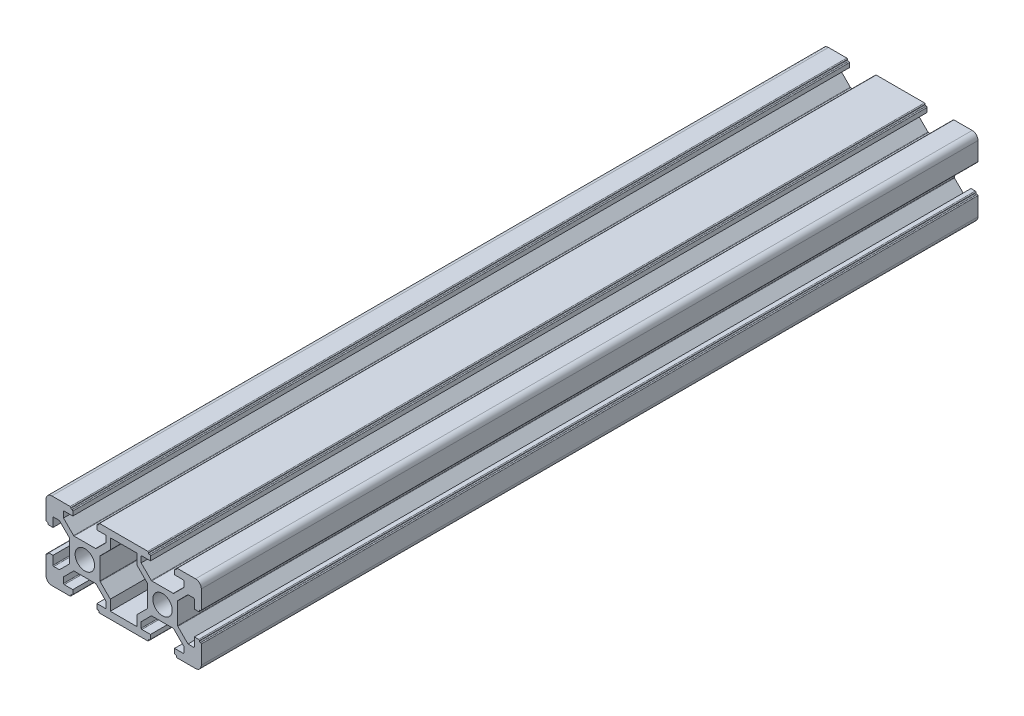
SolidWorks part; units mm, degrees
ref_plane "前视基准面" through (0, 0, 0) normal (0, 0, 1) x (1, 0, 0)
ref_plane "上视基准面" through (0, 0, 0) normal (0, 1, 0) x (1, 0, 0)
ref_plane "右视基准面" through (0, 0, 0) normal (1, 0, 0) x (0, 0, -1)
sketch "Sketch1" plane through (0, 0, 0) normal (0, 0, 1) x (1, 0, 0)
  line L0 (-8.5, 10) -> (-3.8, 10)
  line L3 (-8.5, -10) -> (-3.8, -10)
  line L5 (-10, 8.5) -> (-10, 3.8)
  line L6 (-2.7565, 3.9) -> (2.7565, 3.9)
  line L9 (-2.7565, -3.9) -> (2.7565, -3.9)
  line L10 (3.9, 2.7565) -> (3.9, -2.7565)
  line L11 (-3.9, 2.7565) -> (-3.9, -2.7565)
  line L12 (-3.9586, -2.8979) -> (-6.5607, -5.5)
  line L13 (3.6, 9.7) -> (3.6, 9.8)
  line L14 (3.1, -8.2) -> (5.3, -8.2)
  line L15 (-2.8979, -3.9586) -> (-5.5, -6.5607)
  line L16 (-3.1, -8.2) -> (-3.1, -9.3)
  line L17 (3.1, -8.2) -> (3.1, -9.3)
  line L18 (-5.5, -6.5607) -> (-5.5, -8)
  line L19 (5.5, -6.5607) -> (5.5, -8)
  line L20 (-5.3, -8.2) -> (-3.1, -8.2)
  line L21 (-3.4, -9.5) -> (-3.3, -9.5)
  line L22 (3.8, -10) -> (8.5, -10)
  line L23 (3.3, -9.5) -> (3.4, -9.5)
  line L24 (-3.6, -9.7) -> (-3.6, -9.8)
  line L25 (3.6, -9.7) -> (3.6, -9.8)
  line L26 (-6.5607, -5.5) -> (-8, -5.5)
  line L27 (-9.7, -3.6) -> (-9.8, -3.6)
  line L28 (-9.5, -3.4) -> (-9.5, -3.3)
  line L29 (-8.2, -3.1) -> (-9.3, -3.1)
  line L30 (-8.2, -5.3) -> (-8.2, -3.1)
  line L31 (-10, -3.8) -> (-10, -8.5)
  line L33 (3.8, 10) -> (8.5, 10)
  line L34 (2.8979, -3.9586) -> (5.5, -6.5607)
  line L40 (3.9586, -2.8979) -> (6.5607, -5.5)
  line L41 (3.3, 9.5) -> (3.4, 9.5)
  line L42 (30, 8.5) -> (30, 3.8)
  line L43 (3.1, 8.2) -> (3.1, 9.3)
  line L44 (3.1, 8.2) -> (5.3, 8.2)
  line L45 (5.5, 6.5607) -> (5.5, 8)
  line L46 (2.8979, 3.9586) -> (5.5, 6.5607)
  line L52 (3.9586, 2.8979) -> (6.5607, 5.5)
  line L53 (-3.6, 9.7) -> (-3.6, 9.8)
  line L54 (-3.4, 9.5) -> (-3.3, 9.5)
  line L55 (-3.1, 8.2) -> (-3.1, 9.3)
  line L56 (-5.3, 8.2) -> (-3.1, 8.2)
  line L57 (-5.5, 6.5607) -> (-5.5, 8)
  line L58 (-2.8979, 3.9586) -> (-5.5, 6.5607)
  line L59 (-9.5, 3.4) -> (-9.5, 3.3)
  line L60 (-9.7, 3.6) -> (-9.8, 3.6)
  line L61 (-8.2, 3.1) -> (-9.3, 3.1)
  line L62 (-8.2, 5.3) -> (-8.2, 3.1)
  line L63 (-6.5607, 5.5) -> (-8, 5.5)
  line L64 (-3.9586, 2.8979) -> (-6.5607, 5.5)
  line L65 (29.7, 3.6) -> (29.8, 3.6)
  line L66 (29.5, 3.4) -> (29.5, 3.3)
  line L67 (28.2, 3.1) -> (29.3, 3.1)
  line L68 (28.2, 5.3) -> (28.2, 3.1)
  line L69 (26.5607, 5.5) -> (28, 5.5)
  line L70 (23.9586, 2.8979) -> (26.5607, 5.5)
  line L71 (23.9, 2.7565) -> (23.9, -2.7565)
  line L72 (23.9586, -2.8979) -> (26.5607, -5.5)
  line L73 (26.5607, -5.5) -> (28, -5.5)
  line L74 (28.2, -5.3) -> (28.2, -3.1)
  line L75 (28.2, -3.1) -> (29.3, -3.1)
  line L76 (29.5, -3.4) -> (29.5, -3.3)
  line L77 (29.7, -3.6) -> (29.8, -3.6)
  line L78 (30, -3.8) -> (30, -8.5)
  line L79 (28.5, -10) -> (23.8, -10)
  line L80 (23.6, -9.7) -> (23.6, -9.8)
  line L81 (23.4, -9.5) -> (23.3, -9.5)
  line L82 (23.1, -8.2) -> (23.1, -9.3)
  line L83 (25.3, -8.2) -> (23.1, -8.2)
  line L84 (25.5, -6.5607) -> (25.5, -8)
  line L85 (22.8979, -3.9586) -> (25.5, -6.5607)
  line L86 (22.7565, -3.9) -> (17.2435, -3.9)
  line L87 (17.1021, -3.9586) -> (14.5, -6.5607)
  line L88 (14.5, -6.5607) -> (14.5, -8)
  line L89 (16.9, -8.2) -> (14.7, -8.2)
  line L90 (16.9, -8.2) -> (16.9, -9.3)
  line L91 (16.7, -9.5) -> (16.6, -9.5)
  line L92 (16.4, -9.7) -> (16.4, -9.8)
  line L93 (16.2, -10) -> (11.5, -10)
  line L94 (13.4393, 5.5) -> (13.4393, 8.2)
  line L96 (6.5607, 5.5) -> (6.5607, 8.2)
  line L97 (6.5607, 8.2) -> (13.4393, 8.2)
  line L99 (16.0414, -2.8979) -> (13.4393, -5.5)
  line L100 (16.1, 2.7565) -> (16.1, -2.7565)
  line L101 (16.0414, 2.8979) -> (13.4393, 5.5)
  line L107 (16.2, 10) -> (11.5, 10)
  line L108 (16.4, 9.7) -> (16.4, 9.8)
  line L109 (16.7, 9.5) -> (16.6, 9.5)
  line L110 (16.9, 8.2) -> (16.9, 9.3)
  line L111 (16.9, 8.2) -> (14.7, 8.2)
  line L112 (14.5, 6.5607) -> (14.5, 8)
  line L113 (17.1021, 3.9586) -> (14.5, 6.5607)
  line L114 (22.7565, 3.9) -> (17.2435, 3.9)
  line L115 (22.8979, 3.9586) -> (25.5, 6.5607)
  line L116 (25.5, 6.5607) -> (25.5, 8)
  line L117 (25.3, 8.2) -> (23.1, 8.2)
  line L118 (23.1, 8.2) -> (23.1, 9.3)
  line L119 (23.4, 9.5) -> (23.3, 9.5)
  line L120 (23.6, 9.7) -> (23.6, 9.8)
  line L121 (28.5, 10) -> (23.8, 10)
  line L122 (13.4393, -5.5) -> (13.4393, -8.2)
  line L124 (6.5607, -5.5) -> (6.5607, -8.2)
  line L125 (6.5607, -8.2) -> (13.4393, -8.2)
  line L127 (8.5, 10) -> (11.5, 10)
  line L128 (8.5, -10) -> (11.5, -10)
  arc A3 (-8.5, -10) -> (-10, -8.5) centre (-8.5, -8.5) cw
  arc A4 (-10, 8.5) -> (-8.5, 10) centre (-8.5, 8.5) cw
  arc A5 (3.4, -9.5) -> (3.6, -9.7) centre (3.4, -9.7) cw
  arc A6 (3.8, -10) -> (3.6, -9.8) centre (3.8, -9.8) cw
  arc A7 (3.3, -9.5) -> (3.1, -9.3) centre (3.3, -9.3) cw
  arc A8 (5.3, -8.2) -> (5.5, -8) centre (5.3, -8) ccw
  arc A9 (-3.9, -2.7565) -> (-3.9586, -2.8979) centre (-4.1, -2.7565) cw
  arc A10 (-3.9, 2.7565) -> (-3.9586, 2.8979) centre (-4.1, 2.7565) ccw
  arc A11 (-2.7565, 3.9) -> (-2.8979, 3.9586) centre (-2.7565, 4.1) cw
  arc A12 (2.7565, 3.9) -> (2.8979, 3.9586) centre (2.7565, 4.1) ccw
  arc A13 (3.9586, 2.8979) -> (3.9, 2.7565) centre (4.1, 2.7565) ccw
  arc A14 (3.9, -2.7565) -> (3.9586, -2.8979) centre (4.1, -2.7565) ccw
  arc A15 (-2.8979, -3.9586) -> (-2.7565, -3.9) centre (-2.7565, -4.1) cw
  arc A16 (2.7565, -3.9) -> (2.8979, -3.9586) centre (2.7565, -4.1) cw
  arc A17 (-3.6, -9.8) -> (-3.8, -10) centre (-3.8, -9.8) cw
  arc A18 (-3.3, -9.5) -> (-3.1, -9.3) centre (-3.3, -9.3) ccw
  arc A19 (-3.6, -9.7) -> (-3.4, -9.5) centre (-3.4, -9.7) cw
  arc A20 (-8.2, 5.3) -> (-8, 5.5) centre (-8, 5.3) cw
  arc A23 (-8.2, -5.3) -> (-8, -5.5) centre (-8, -5.3) ccw
  arc A24 (-5.3, -8.2) -> (-5.5, -8) centre (-5.3, -8) cw
  arc A31 (3.1, 9.3) -> (3.3, 9.5) centre (3.3, 9.3) cw
  arc A32 (3.6, 9.8) -> (3.8, 10) centre (3.8, 9.8) cw
  arc A33 (3.6, 9.7) -> (3.4, 9.5) centre (3.4, 9.7) cw
  arc A34 (-3.8, 10) -> (-3.6, 9.8) centre (-3.8, 9.8) cw
  arc A35 (-3.3, 9.5) -> (-3.1, 9.3) centre (-3.3, 9.3) cw
  arc A36 (-3.4, 9.5) -> (-3.6, 9.7) centre (-3.4, 9.7) cw
  arc A37 (5.5, 8) -> (5.3, 8.2) centre (5.3, 8) ccw
  arc A38 (-5.5, 8) -> (-5.3, 8.2) centre (-5.3, 8) cw
  arc A39 (-10, 3.8) -> (-9.8, 3.6) centre (-9.8, 3.8) ccw
  arc A40 (-9.5, 3.3) -> (-9.3, 3.1) centre (-9.3, 3.3) ccw
  arc A41 (-9.7, 3.6) -> (-9.5, 3.4) centre (-9.7, 3.4) cw
  arc A42 (-10, -3.8) -> (-9.8, -3.6) centre (-9.8, -3.8) cw
  arc A43 (-9.5, -3.3) -> (-9.3, -3.1) centre (-9.3, -3.3) cw
  arc A44 (-9.5, -3.4) -> (-9.7, -3.6) centre (-9.7, -3.4) cw
  arc A45 (30, 8.5) -> (28.5, 10) centre (28.5, 8.5) ccw
  arc A46 (30, 3.8) -> (29.8, 3.6) centre (29.8, 3.8) cw
  arc A47 (29.7, 3.6) -> (29.5, 3.4) centre (29.7, 3.4) ccw
  arc A48 (29.5, 3.3) -> (29.3, 3.1) centre (29.3, 3.3) cw
  arc A49 (28.2, 5.3) -> (28, 5.5) centre (28, 5.3) ccw
  arc A50 (23.9, 2.7565) -> (23.9586, 2.8979) centre (24.1, 2.7565) cw
  arc A51 (23.9, -2.7565) -> (23.9586, -2.8979) centre (24.1, -2.7565) ccw
  arc A52 (28.2, -5.3) -> (28, -5.5) centre (28, -5.3) cw
  arc A53 (29.5, -3.3) -> (29.3, -3.1) centre (29.3, -3.3) ccw
  arc A54 (29.5, -3.4) -> (29.7, -3.6) centre (29.7, -3.4) ccw
  arc A55 (30, -3.8) -> (29.8, -3.6) centre (29.8, -3.8) ccw
  arc A56 (28.5, -10) -> (30, -8.5) centre (28.5, -8.5) ccw
  arc A57 (23.6, -9.8) -> (23.8, -10) centre (23.8, -9.8) ccw
  arc A58 (23.6, -9.7) -> (23.4, -9.5) centre (23.4, -9.7) ccw
  arc A59 (23.3, -9.5) -> (23.1, -9.3) centre (23.3, -9.3) cw
  arc A60 (25.3, -8.2) -> (25.5, -8) centre (25.3, -8) ccw
  arc A61 (22.8979, -3.9586) -> (22.7565, -3.9) centre (22.7565, -4.1) ccw
  arc A62 (17.2435, -3.9) -> (17.1021, -3.9586) centre (17.2435, -4.1) ccw
  arc A63 (14.7, -8.2) -> (14.5, -8) centre (14.7, -8) cw
  arc A64 (16.7, -9.5) -> (16.9, -9.3) centre (16.7, -9.3) ccw
  arc A65 (16.6, -9.5) -> (16.4, -9.7) centre (16.6, -9.7) ccw
  arc A66 (16.2, -10) -> (16.4, -9.8) centre (16.2, -9.8) ccw
  arc A72 (16.1, -2.7565) -> (16.0414, -2.8979) centre (15.9, -2.7565) cw
  arc A73 (16.0414, 2.8979) -> (16.1, 2.7565) centre (15.9, 2.7565) cw
  arc A79 (16.4, 9.8) -> (16.2, 10) centre (16.2, 9.8) ccw
  arc A80 (16.4, 9.7) -> (16.6, 9.5) centre (16.6, 9.7) ccw
  arc A81 (16.9, 9.3) -> (16.7, 9.5) centre (16.7, 9.3) ccw
  arc A82 (14.5, 8) -> (14.7, 8.2) centre (14.7, 8) cw
  arc A83 (17.2435, 3.9) -> (17.1021, 3.9586) centre (17.2435, 4.1) cw
  arc A84 (22.7565, 3.9) -> (22.8979, 3.9586) centre (22.7565, 4.1) ccw
  arc A85 (25.5, 8) -> (25.3, 8.2) centre (25.3, 8) ccw
  arc A86 (23.3, 9.5) -> (23.1, 9.3) centre (23.3, 9.3) ccw
  arc A87 (23.4, 9.5) -> (23.6, 9.7) centre (23.4, 9.7) ccw
  arc A88 (23.8, 10) -> (23.6, 9.8) centre (23.8, 9.8) ccw
  point P11 (3.9, 3.9)
  point P19 (3.3697, 4.4303)
  point P20 (-10.6428, -10.6428)
  point P25 (-11.1731, -10.1124)
  point P26 (4.4303, 3.3697)
  point P28 (-10.1124, -11.1731)
  dimension "D3" = 0.2
  dimension "D4" = 0.2
  dimension "D5" = 0.2
  dimension "D8" = 0.2
  dimension "D9" = 0.2
  dimension "D10" = 0.2
  dimension "D6" = 1.8
  dimension "D7" = 0.5
extrude "Boss-Extrude1" add sketch "Sketch1" along normal blind 200
ref_plane "hole" through (0, 0, 200) normal (0, 0, 1) x (1, 0, 0)
sketch "Sketch2" plane through (0, 0, 200) normal (0, 0, 1) x (1, 0, 0)
  circle A0 centre (0, 0) radius 2.5
  circle A1 centre (20, 0) radius 2.5
  dimension "D1" = 5
extrude "Cut-Extrude1" cut sketch "Sketch2" against normal through all
sketch "Sketch3" plane through (0, -3.9, 0) normal (0, -1, 0) x (1, 0, 0)
  line L0 (17.2435, 200) -> (22.7565, 200) construction
  line L1 (20, 200) -> (0, 200) construction
  line L2 (-2.7565, 200) -> (2.7565, 200) construction
  line L3 (10, 200) -> (10, 151.4468) construction
  circle A0 centre (20, 183.3) radius 1.5
  circle A1 centre (20, 166.6) radius 1.5
  circle A2 centre (0, 166.6) radius 1.5
  circle A3 centre (0, 183.3) radius 1.5
  point P6 (20, 200)
  dimension "D1" = 0
  dimension "D2" = 0
  dimension "D3" = 16.7
  dimension "D4" = 16.7
  dimension "D5" = 3
  dimension "D6" = 3
extrude "Cut-Extrude2" cut sketch "Sketch3" against normal blind 10
sketch "Sketch4" plane through (0, -10, 0) normal (0, -1, 0) x (1, 0, 0)
  text T0 "x bottom"
extrude "Cut-Extrude3" cut sketch "Sketch4" against normal blind 1
